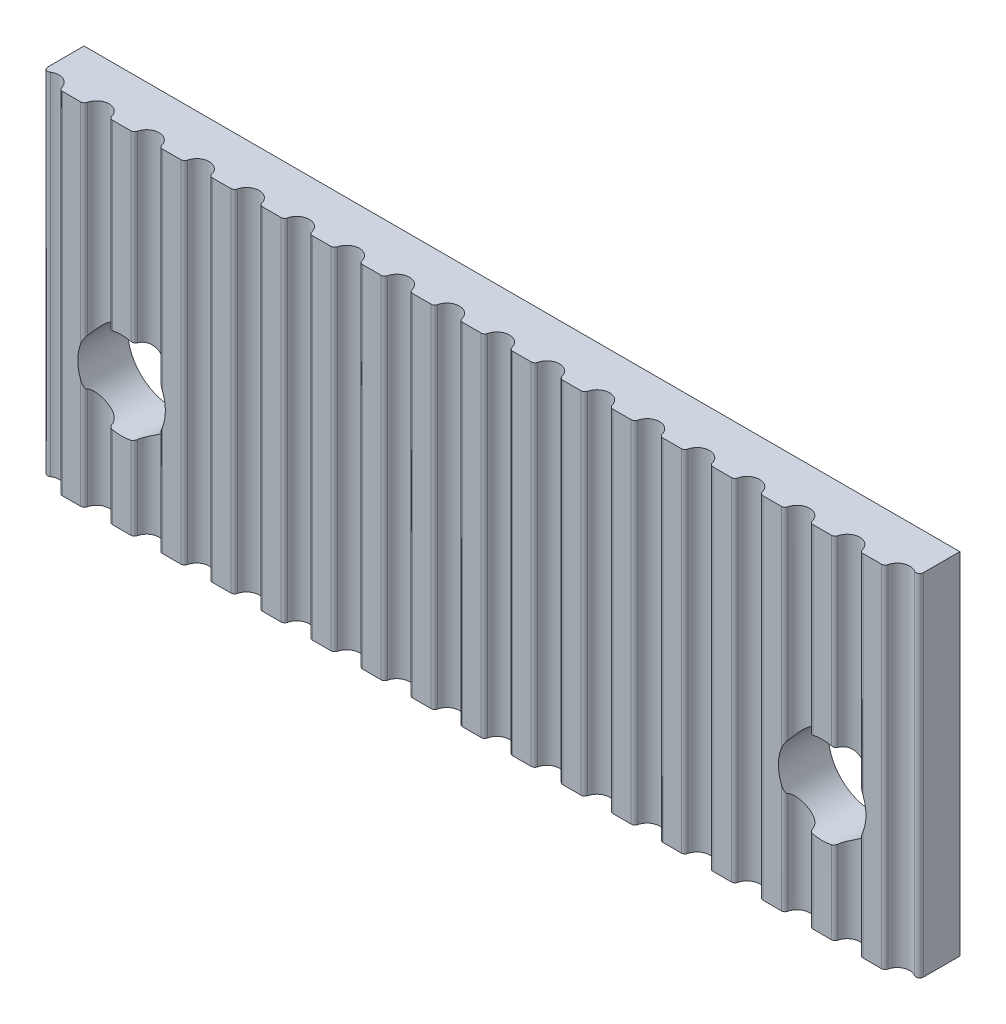
SolidWorks part; units mm, degrees
material "ABS"
ref_plane "Front Plane" through (0, 0, 0) normal (0, 0, 1) x (1, 0, 0)
ref_plane "Top Plane" through (0, 0, 0) normal (0, 1, 0) x (1, 0, 0)
ref_plane "Right Plane" through (0, 0, 0) normal (1, 0, 0) x (0, 0, -1)
sketch "Sketch1" plane through (0, 0, 0) normal (0, 1, 0) x (1, 0, 0)
  line L1 (-17.5, -1) -> (17.5, -1)
  line L2 (-17.5, -1) -> (-17.5, 1)
  line L3 (-17.5, 1) -> (17.5, 1)
  line L4 (17.5, -1) -> (17.5, 1)
  line L5 (-17.5, -1) -> (17.5, 1) construction
  line L6 (-17.5, 1) -> (17.5, -1) construction
  point P0 (0, 0)
  dimension "D1" = 2
  dimension "D2" = 35
extrude "Boss-Extrude1" add sketch "Sketch1" along normal blind 14
sketch "Sketch2" plane through (0, 0, 1) normal (0, 0, 1) x (1, 0, 0)
  line L0 (-17.5, 14) -> (-17.5, 0) construction
  line L1 (-17.5, 0) -> (17.5, 0) construction
  line L2 (17.5, 14) -> (17.5, 0) construction
  circle A0 centre (-14, 5) radius 1.75
  circle A1 centre (14, 5) radius 1.75
  dimension "D1" = 3.5
  dimension "D3" = 5
  dimension "D4" = 3.5
  dimension "D2" = 3.5
  dimension "D5" = 3.5
extrude "Cut-Extrude1" cut sketch "Sketch2" against normal blind 14
sketch "Sketch3" plane through (0, 14, 0) normal (0, 1, 0) x (1, 0, 0)
  line L0 (-17.5, -1) -> (17.5, -1) construction
  circle A0 centre (-17, -1) radius 0.5
  dimension "D1" = 1
extrude "Cut-Extrude2" cut sketch "Sketch3" against normal through all
pattern_linear "LPattern1" count 18 spacing 2 along (1, 0, 0) of "Cut-Extrude2"
fillet "Fillet1" radius 0.15 44 edges at (-16.5, 7, 1) (-17.5, 7, 1) (-14.5, 10.3385, 1) (-15.5, 9.9507, 1) (13.5, 1.6615, 1) (12.5, 2.0493, 1) (15.5, 2.0493, 1) (14.5, 1.6615, 1) (17.5, 7, 1) (16.5, 7, 1) (15.5, 9.9507, 1) (14.5, 10.3385, 1) (13.5, 10.3385, 1) (12.5, 9.9507, 1) (11.5, 7, 1) (10.5, 7, 1) (9.5, 7, 1) (8.5, 7, 1) (7.5, 7, 1) (6.5, 7, 1) (5.5, 7, 1) (4.5, 7, 1) (3.5, 7, 1) (2.5, 7, 1) (1.5, 7, 1) (0.5, 7, 1) (-0.5, 7, 1) (-1.5, 7, 1) (-2.5, 7, 1) (-3.5, 7, 1) (-4.5, 7, 1) (-5.5, 7, 1) (-6.5, 7, 1) (-7.5, 7, 1) (-8.5, 7, 1) (-9.5, 7, 1) (-12.5, 9.9507, 1) (-13.5, 10.3385, 1) (-10.5, 7, 1) (-11.5, 7, 1) (-12.5, 2.0493, 1) (-13.5, 1.6615, 1) (-14.5, 1.6615, 1) (-15.5, 2.0493, 1)
